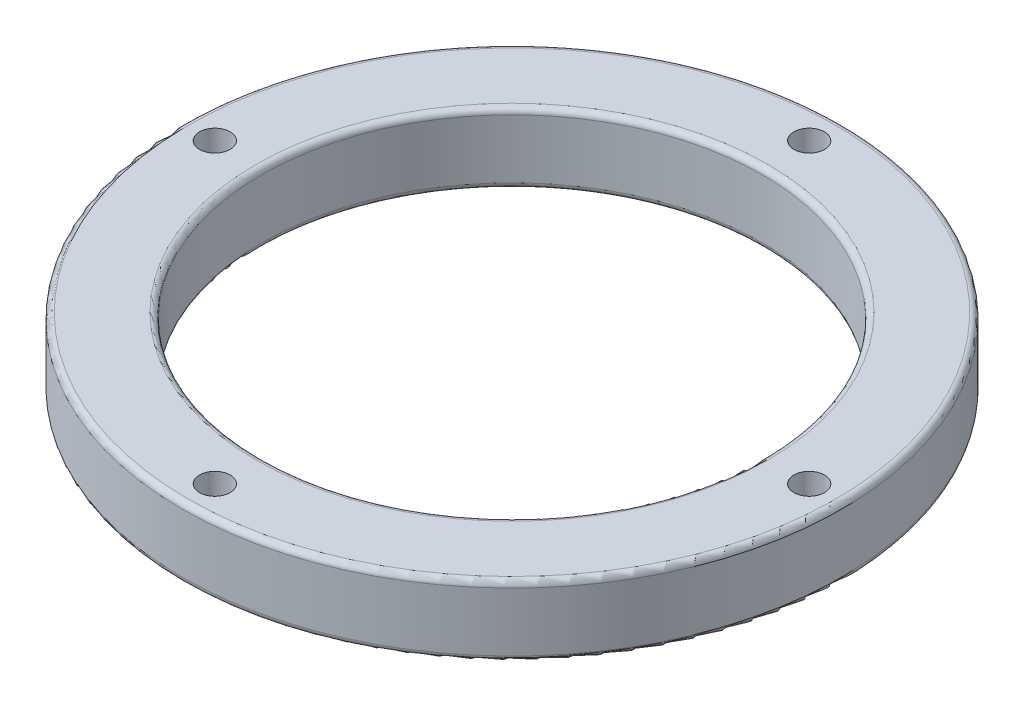
SolidWorks part; units mm, degrees
material "PLA"
ref_plane "前视基准面" through (0, 0, 0) normal (0, 0, 1) x (1, 0, 0)
ref_plane "上视基准面" through (0, 0, 0) normal (0, 1, 0) x (1, 0, 0)
ref_plane "右视基准面" through (0, 0, 0) normal (1, 0, 0) x (0, 0, -1)
sketch "草图3" plane through (0, 0, 0) normal (0, 1, 0) x (1, 0, 0)
  circle A0 centre (0, 0) radius 56
  circle A1 centre (0, 0) radius 42.5
  circle A2 centre (0, 0) radius 50.5 construction
  circle A3 centre (50.5, 0) radius 2.6
  circle A4 centre (0, -50.5) radius 2.6
  circle A5 centre (-50.5, 0) radius 2.6
  circle A6 centre (0, 50.5) radius 2.6
  point P15 (0, 0)
  dimension "D1" = 85
  dimension "D2" = 112
  dimension "D3" = 101
  dimension "D5" = 5.2
  dimension "D4" = 4
extrude "凸台-拉伸1" add sketch "草图3" along normal blind 12
fillet "圆角1" radius 1 4 edges at (0, 0, 56) (0, 12, 56) (0, 0, 42.5) (0, 12, 42.5)
